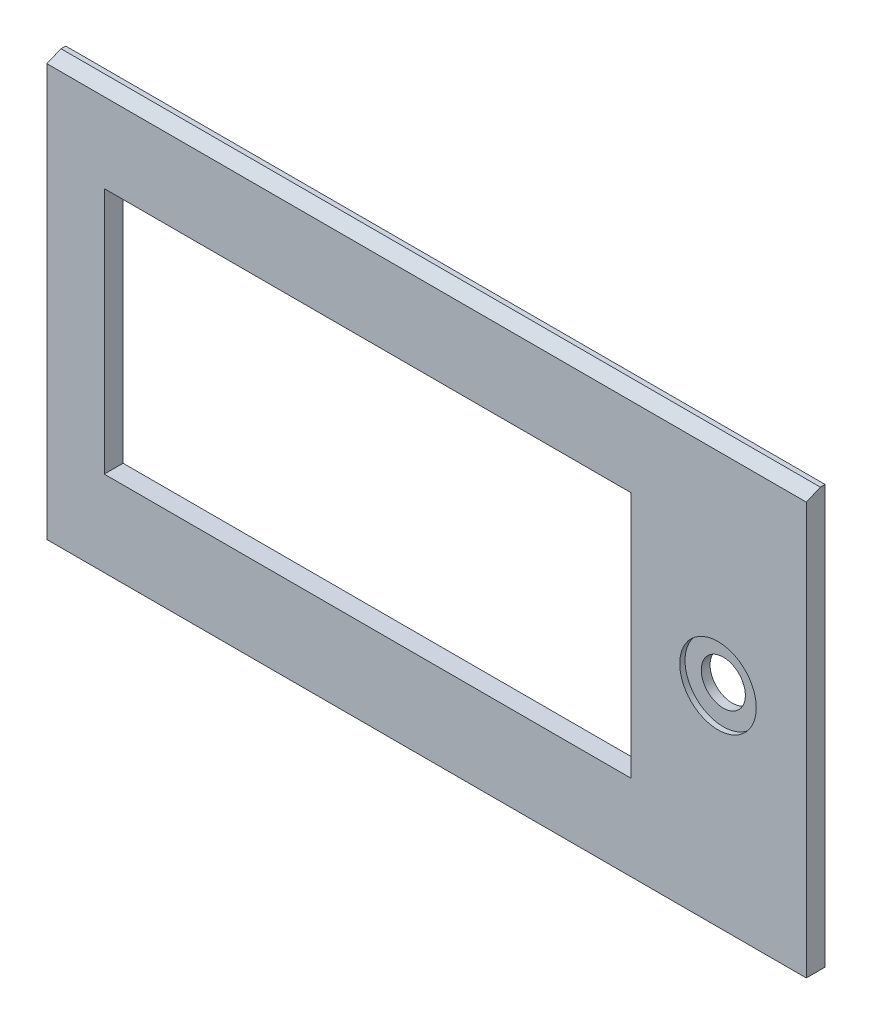
SolidWorks part; units mm, degrees
material "ABS"
ref_plane "Front Plane" through (0, 0, 0) normal (0, 0, 1) x (1, 0, 0)
ref_plane "Top Plane" through (0, 0, 0) normal (0, 1, 0) x (1, 0, 0)
ref_plane "Right Plane" through (0, 0, 0) normal (1, 0, 0) x (0, 0, -1)
sketch "Sketch1" plane through (0, 0, 0) normal (0, 0, 1) x (1, 0, 0)
  line L0 (-9.75, 56.5) -> (99.25, 56.5)
  line L1 (0, 0) -> (89.5, 0)
  line L2 (0, 0) -> (0, 42)
  line L3 (0, 42) -> (89.5, 42)
  line L4 (89.5, 0) -> (89.5, 42)
  line L5 (-4.75, 51.5) -> (94.25, 51.5) construction
  line L6 (-4.75, 51.5) -> (-4.75, -9.5) construction
  line L7 (-4.75, -9.5) -> (94.25, -9.5) construction
  line L8 (94.25, 51.5) -> (94.25, -9.5) construction
  line L9 (99.25, 56.5) -> (99.25, -14.5) construction
  line L10 (-9.75, -14.5) -> (99.25, -14.5)
  line L11 (-9.75, 56.5) -> (-9.75, -14.5)
  line L13 (99.25, 56.5) -> (119.25, 56.5)
  line L14 (99.25, 56.5) -> (99.25, -14.5) construction
  line L15 (99.25, -14.5) -> (119.25, -14.5)
  line L16 (119.25, 56.5) -> (119.25, -14.5)
  circle A0 centre (104.25, 21) radius 3.75
  circle A1 centre (104.25, 21) radius 7.5 construction
  point P9 (44.75, 0)
  point P10 (44.75, -9.5)
  point P11 (-4.75, 21)
  point P12 (0, 21)
  point P22 (89.5, 21)
  dimension "D7" = 7.5
  dimension "D8" = 15
  dimension "D1" = 89.5
  dimension "D2" = 42
  dimension "D3" = 61
  dimension "D4" = 99
  dimension "D6" = 20
  dimension "D9" = 10
  dimension "D10" = 7.5
  dimension "D11" = 129
  dimension "D12" = 71
  dimension "D5" = 5
extrude "Boss-Extrude1" add sketch "Sketch1" along normal blind 3.2 contours L16 L13 L0 L11 L10 L15 L4 L1 L2 L3
chamfer "Chamfer1" distance 2.4 angle 22.5 1 edges at (54.75, 56.5, 3.2)
sketch "Sketch3" plane through (0, 0, 0) normal (0, 0, -1) x (-1, 0, 0)
  line L1 (-111.75, 13.5) -> (-96.75, 13.5)
  line L2 (-111.75, 13.5) -> (-111.75, 28.5)
  line L3 (-111.75, 28.5) -> (-96.75, 28.5)
  line L4 (-96.75, 13.5) -> (-96.75, 28.5)
  point P4 (-96.75, 21)
  point P6 (-104.25, 28.5)
  point P7 (-104.25, 21)
  dimension "D1" = 15
extrude "Cut-Extrude2" cut sketch "Sketch3" against normal blind 0.8
sketch "Sketch4" plane through (0, 0, 3.2) normal (0, 0, 1) x (1, 0, 0)
  circle A0 centre (104.25, 21) radius 6.5
  dimension "D1" = 13
extrude "Cut-Extrude3" cut sketch "Sketch4" against normal offset from surface (0.9 mm away) 1.5 up to face at (108, 21, 0.8)
